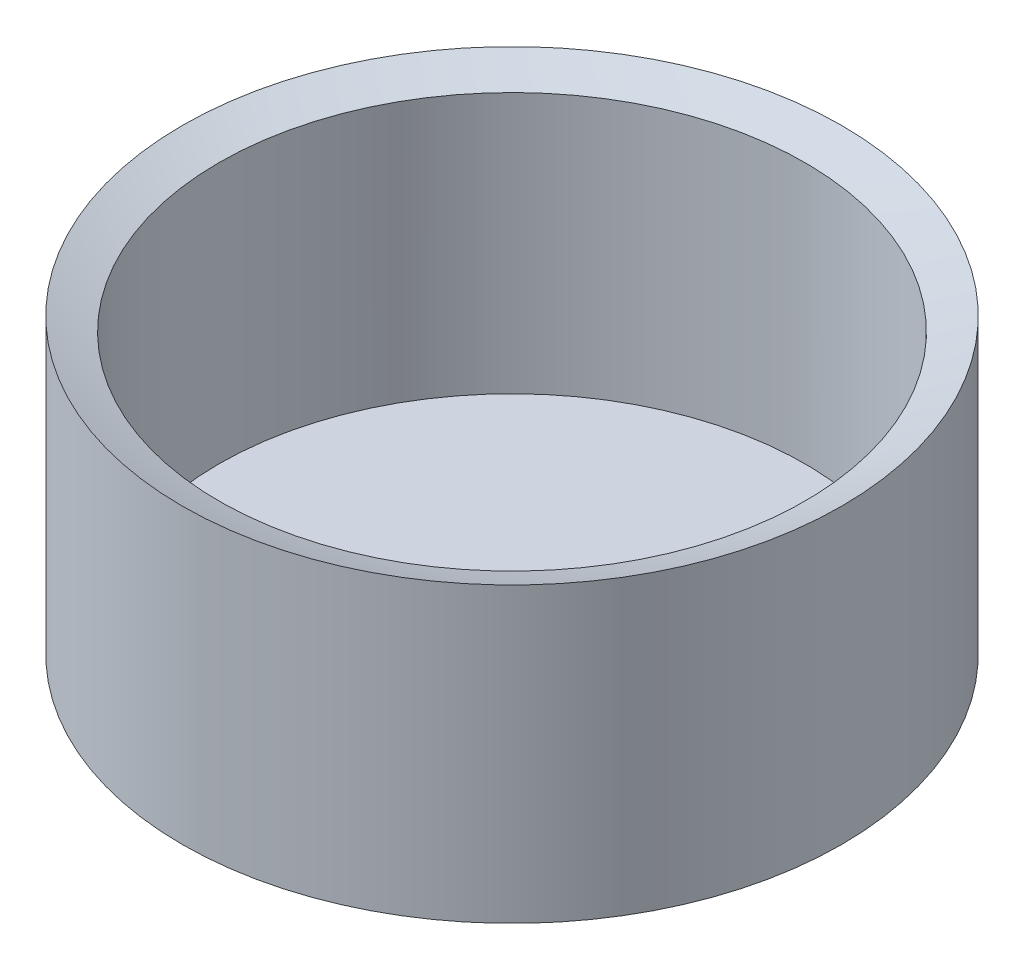
SolidWorks part; units mm, degrees
ref_plane "Front Plane" through (0, 0, 0) normal (0, 0, 1) x (1, 0, 0)
ref_plane "Top Plane" through (0, 0, 0) normal (0, 1, 0) x (1, 0, 0)
ref_plane "Right Plane" through (0, 0, 0) normal (1, 0, 0) x (0, 0, -1)
sketch "Sketch1" plane through (0, 0, 0) normal (0, 0, 1) x (1, 0, 0)
  line L0 (-50.8, 50.8) -> (-50.8, 0) construction
  line L1 (0, 0) -> (6.35, 0)
  line L2 (0, 0) -> (0, 50.8)
  line L3 (0, 50.8) -> (6.35, 50.8)
  line L4 (6.35, 0) -> (6.35, 50.8)
  dimension "D1" = 6.35
  dimension "D2" = 50.8
  dimension "D3" = 57.15
revolve "Revolve1" add sketch "Sketch1" angle 360 about L0
sketch "Sketch2" plane through (0, 0, 0) normal (0, 1, 0) x (1, 0, 0)
  circle A0 centre (-50.8, 0) radius 57.15 construction
  circle A1 centre (-50.8, 0) radius 57.15
extrude "Boss-Extrude1" add sketch "Sketch2" along normal blind 3.175
ref_plane "Plane1" through (-50.8, 0, 0) normal (1, 0, 0) x (0, 0, -1)
sketch "Sketch4" plane through (0, 0, 0) normal (0, 0, 1) x (1, 0, 0)
  line L0 (-50.8, 46.2305) -> (-50.8, 148.8163) construction
  line L1 (-50.8, -27.94) -> (-50.8, 27.94) construction
  line L2 (-107.95, 50.8) -> (-50.8, 50.8)
  line L3 (0, 50.8) -> (-101.6, 50.8) construction
  line L4 (-50.8, 50.8) -> (-50.8, 39.6786)
  arc A1 (-107.95, 50.8) -> (-50.8, 39.6786) centre (-50.8, 192.0786) ccw
  dimension "D1" = 152.4
revolve "Cut-Revolve1" cut sketch "Sketch4" angle 360 about L0
